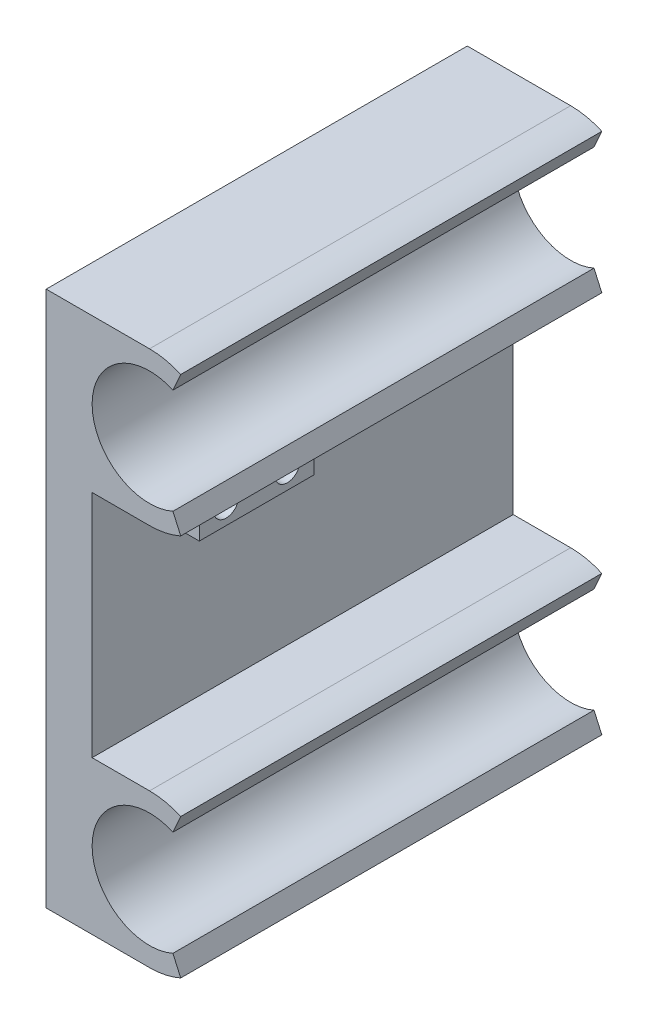
SolidWorks part; units mm, degrees
ref_plane "Plano frontal" through (0, 0, 0) normal (0, 0, 1) x (1, 0, 0)
ref_plane "Plano superior" through (0, 0, 0) normal (0, 1, 0) x (1, 0, 0)
ref_plane "Plano direito" through (0, 0, 0) normal (1, 0, 0) x (0, 0, -1)
sketch "Esboço1" plane through (0, 0, 0) normal (0, 0, 1) x (1, 0, 0)
  line L0 (0, 0) -> (67.7245, 0) construction
  line L1 (0, 35) -> (0, -35)
  line L2 (13.5, -25) -> (26.7005, -25) construction
  line L3 (16.5541, 18.15) -> (17.5721, 15.8667)
  line L4 (13.5, 15) -> (6, 15)
  line L5 (16.5541, -31.85) -> (17.5721, -34.1333)
  line L6 (6, -15) -> (6, 15)
  line L7 (13.5, -35) -> (0, -35)
  line L8 (13.5, 25) -> (26.7005, 25) construction
  line L9 (13.5, -15) -> (6, -15)
  line L10 (13.5, 35) -> (0, 35)
  line L11 (16.5541, -18.15) -> (17.5721, -15.8667)
  line L16 (16.5541, 31.85) -> (17.5721, 34.1333)
  arc A0 (16.5541, 31.85) -> (16.5541, 18.15) centre (13.5, 25) ccw
  arc A1 (17.5721, -34.1333) -> (13.5, -35) centre (13.5, -25) cw
  arc A2 (13.5, 15) -> (17.5721, 15.8667) centre (13.5, 25) ccw
  arc A3 (13.5, -15) -> (17.5721, -15.8667) centre (13.5, -25) cw
  arc A4 (16.5541, -31.85) -> (16.5541, -18.15) centre (13.5, -25) cw
  arc A5 (17.5721, 34.1333) -> (13.5, 35) centre (13.5, 25) ccw
  point P3 (0, 0)
  dimension "D1" = 15
  dimension "D2" = 13.7
  dimension "D5" = 10
  dimension "D3" = 6
  dimension "D4" = 70
extrude "Ressalto-extrusão1" add sketch "Esboço1" along normal blind 55
sketch "Esboço3" plane through (6, 0, 0) normal (1, 0, 0) x (0, 0, -1)
  line L0 (-55, -15) -> (-55, 15) construction
  line L1 (-51, 12.5) -> (-36, 12.5)
  line L2 (-51, 12.5) -> (-51, 17.5)
  line L3 (-51, 17.5) -> (-36, 17.5)
  line L4 (-36, 12.5) -> (-36, 17.5)
  line L5 (-55, 17.5) -> (0, 17.5) construction
  line L6 (-55, 32.5) -> (-55, 17.5) construction
  line L7 (0, 17.5) -> (0, 32.5) construction
  line L8 (-55, 25) -> (0, 25) construction
  line L9 (0, 0) -> (-55, 0) construction
  line L10 (-27.5, 35) -> (-27.5, -35) construction
  line L11 (-55, 35) -> (0, 35) construction
  line L12 (-55, -35) -> (0, -35) construction
  line L13 (-43.5, 17.5) -> (-43.5, 12.5) construction
  circle A0 centre (-47.5, 15) radius 1.65
  circle A1 centre (-39.5, 15) radius 1.65
  point P27 (-51, 15)
  dimension "D5" = 3.3
  dimension "D1" = 7.5
  dimension "D2" = 8
  dimension "D3" = 40
  dimension "D4" = 15
  dimension "D6" = 30
extrude "Ressalto-extrusão2" add sketch "Esboço3" along normal blind 10
